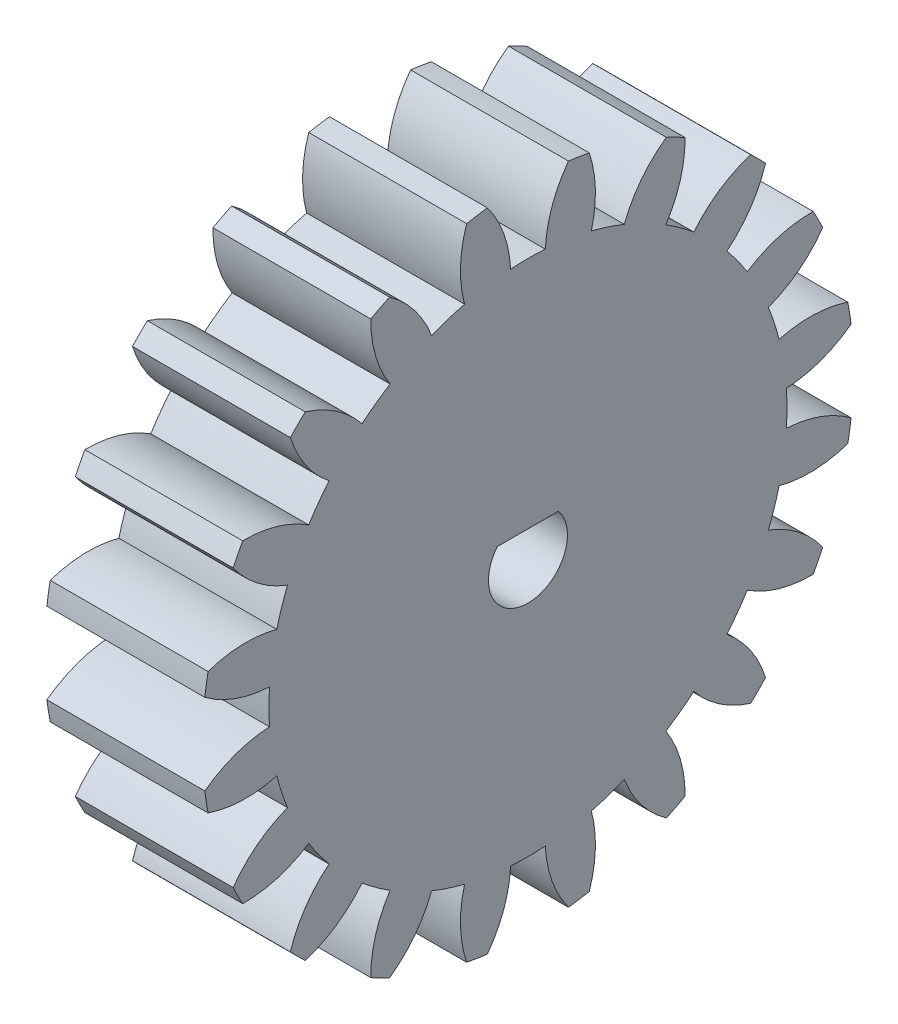
SolidWorks part; units mm, degrees
ref_plane "Plane1" through (0, 0, 0) normal (0, 0, 1) x (1, 0, 0)
ref_plane "Plane2" through (0, 0, 0) normal (0, 1, 0) x (1, 0, 0)
ref_plane "Plane3" through (0, 0, 0) normal (1, 0, 0) x (0, 0, -1)
sketch "HoldingSke" plane through (0, 0, 0) normal (0, 1, 0) x (1, 0, 0)
  line L0 (0, 0) -> (0.6265, -0.228)
  line L1 (-15, 0) -> (100, 0) construction
  line L2 (0, 0) -> (-2.1039, 2.3779)
  line L3 (0, 0) -> (-11.863, 4.5341)
  line L4 (0, 0) -> (8.1152, 2.9537)
  line L5 (0, 0) -> (-46.8476, -17.4728)
  line L6 (0, 0) -> (-6.6317, -4.4744)
  line L7 (-2.1039, 2.3779) -> (8.6586, 51.2059)
  line L8 (-76.2, 54.61) -> (-76.1, 54.61)
  line L9 (-67.7845, 28.3722) -> (-49.3413, 33.142)
  line L10 (-76.2, 71.12) -> (104.1128, 71.12)
  line L11 (0, 0) -> (-8, 0)
  line L12 (-76.2, 101.6) -> (-76.147, 101.6)
  line L13 (24.9733, 27.94) -> (52.9518, 28.4284)
  line L14 (24.9733, 27.94) -> (24.9743, 27.94)
  line L15 (24.9733, 27.94) -> (100.4006, 29.5858)
  line L16 (-63.627, -1.5) -> (-12.827, -1.5)
  circle A0 centre (0, 0) radius 0.4
  circle A1 centre (0, 0) radius 13.124
  circle A2 centre (0, 0) radius 37.5
  circle A3 centre (0, 0) radius 0.4
  dimension "MHD" = 26.248
  dimension "Hub_dia" = 75
  dimension "Bore" = 0.8
  dimension "MBD" = 0.8
  dimension "Num_teeth" = 20
  dimension "Pitch" = 0.6667
  dimension "Overall_len" = 50
  dimension "Show_teeth" = 20
  dimension "Thickness" = 8
  dimension "OAL" = 50.0001
  dimension "T_dim" = 0.1
  dimension "Ap" = 14.5
  dimension "H" = 19.05
  dimension "Pitch_radius" = 180.3128
  dimension "Width" = 8
  dimension "Backlash" = 0.053
  dimension "Addendum_fac" = 1
  dimension "Dedendum_fac" = 1.25
  dimension "Clearance_fac" = 0.25
  dimension "Dedendum_add" = 0.001
  dimension "Module" = 1.5
sketch "BasProSke" plane through (0, 0, 0) normal (0, 1, 0) x (1, 0, 0)
  line L0 (-10, 0) -> (60, 0) construction
  line L1 (0, 0) -> (0, 16.5)
  line L2 (0, 0) -> (8, 0)
  line L3 (8, 0) -> (8, 16.5)
  line L4 (8, 16.5) -> (0, 16.5)
  dimension "Thickness" = 8
  dimension "Diameter" = 33
revolve "Base-Revolve" add sketch "BasProSke" angle 360 about L0
sketch "TooCutSke" plane through (0, 0, 0) normal (1, 0, 0) x (0, 0, -1)
  line L1 (0, 0) -> (0, 107) construction
  line L2 (0, 0) -> (-1.2696, 14.9462) construction
  line L3 (0, 0) -> (-4.6808, 29.5532) construction
  line L4 (-1.2696, 14.9462) -> (-2.3404, 14.7766) construction
  arc A0 (0.8779, 13.0946) -> (-0.8779, 13.0946) centre (0, 0) ccw
  arc A1 (2.0711, 16.3951) -> (-2.0711, 16.3951) centre (0, 0) ccw
  circle A2 centre (0, 0) radius 15 construction
  circle A3 centre (0, 0) radius 14.5222 construction
  arc A4 (-0.8779, 13.0946) -> (-2.0711, 16.3951) centre (-6.8704, 12.7942) ccw
  arc A5 (2.0711, 16.3951) -> (0.8779, 13.0946) centre (6.8704, 12.7942) ccw
  dimension "Root_dia" = 26.248
  dimension "Overcut_dia" = 33.0508
  dimension "Pitch_dia" = 30
  dimension "Base_dia" = 29.0444
  dimension "Flank_rad" = 6
  dimension "Half_ang" = 9
  dimension "Half_CT" = 1.0841
extrude "ToothCut" cut sketch "TooCutSke" along normal through all
fillet "Breaks" [suppressed] radius 0.03
fillet "RootFillets" [suppressed] radius 0.376
pattern_circular "TeethCuts" count 20 every 18 about axis through (-10, 0, 0) along (1, 0, 0) of "ToothCut", "RootFillets", "Breaks"
sketch "HubNeaOneSke" plane through (0, 0, 0) normal (-1, 0, 0) x (0, 0, 1)
  circle A0 centre (0, 0) radius 13.124
  dimension "Diameter" = 26.248
extrude "HubNearOne" [suppressed] add sketch "HubNeaOneSke" along normal blind 42.0001
sketch "HubNeaBotSke" plane through (0, 0, 0) normal (-1, 0, 0) x (0, 0, 1)
  circle A0 centre (0, 0) radius 13.124
  dimension "Diameter" = 26.248
extrude "HubNearBoth" [suppressed] add sketch "HubNeaBotSke" along normal blind 21
ref_plane "FarPln" through (8, 0, 0) normal (1, 0, 0) x (0, 0, -1)
sketch "HubFarSke" plane through (8, 0, 0) normal (1, 0, 0) x (0, 0, -1)
  circle A0 centre (0, 0) radius 13.124
  dimension "Diameter" = 26.248
extrude "HubFar" [suppressed] add sketch "HubFarSke" along normal blind 21
sketch "BorSke" plane through (0, 0, 0) normal (1, 0, 0) x (0, 0, -1)
  circle A0 centre (0, 0) radius 0.4
  dimension "Diameter" = 0.8
extrude "Bore" cut sketch "BorSke" along normal mid plane 100.0001
sketch "KeySke" plane through (0, 0, 0) normal (1, 0, 0) x (0, 0, -1)
  line L0 (-0.05, 0) -> (-0.05, 0.5)
  line L1 (-0.05, 0.5) -> (0.05, 0.5)
  line L2 (0.05, 0.5) -> (0.05, 0)
  line L3 (0, 0) -> (0, 34) construction
  line L4 (-0.05, 0) -> (0.05, 0)
  dimension "Offset" = 0.5
  dimension "Width" = 0.1
extrude "Keyway" [suppressed] cut sketch "KeySke" along normal mid plane 100.0001
pattern_circular "Keyway2" [suppressed] count 2 every 90 about axis through (-10, 0, 0) along (1, 0, 0)
sketch "Sketch1" plane through (8, 0, 0) normal (1, 0, 0) x (0, 0, -1)
  line L0 (1.5537, 1.2594) -> (-1.5537, 1.2594)
  circle A0 centre (0, 0) radius 2
extrude "Cut-Extrude1" cut sketch "Sketch1" against normal through all contours L0 A0
equation "' \"Module@HoldingSke\" = 6.35"
equation "' \"Num_teeth@HoldingSke\" = 12"
equation "' \"Ap@HoldingSke\" =  20"
equation "' \"Ap@HoldingSke\" = 20"
equation "' \"Width@HoldingSke\" = 0.5 * 25.4"
equation "' \"Hub_dia@HoldingSke\"= 1 * 25.4"
equation "' \"Hub_dia@HoldingSke\" = 1 * 25.4"
equation "' \"Overall_len@HoldingSke\" = 1.0 * 25.4"
equation "' \"Bore@HoldingSke\" = 0.75 * 25.4"
equation "' \"T_dim@HoldingSke\" = 0.1 * 25.4"
equation "' \"Width@KeySke\" = 0.25 * 25.4"
equation "' \"Show_teeth@HoldingSke\" = 13"
equation "' \"Backlash@HoldingSke\" = 0.009 * 25.4"
equation "' \"Addendum_fac@HoldingSke\" = 1.0"
equation "' \"Dedendum_fac@HoldingSke\" = 1.25"
equation "' \"Dedendum_add@HoldingSke\" = 0.00005 * 25.4"
equation "' \"Clearance_fac@HoldingSke\" = 0.25"
equation "\"Pitch@HoldingSke\" = 1 / \"Module@HoldingSke\""
equation "\"Overcut_dia@TooCutSke\" = (\"Num_teeth@HoldingSke\" + 2 * \"Addendum_fac@HoldingSke\") / \"Pitch@HoldingSke\" + 0.002 * 25.4"
equation "\"Pitch_dia@TooCutSke\" = \"Num_teeth@HoldingSke\" / \"Pitch@HoldingSke\""
equation "\"Base_dia@TooCutSke\" = \"Num_teeth@HoldingSke\" / \"Pitch@HoldingSke\" * cos((\"Ap@HoldingSke\"  * 3.14159265 / 180))"
equation "\"Root_dia@TooCutSke\" = (\"Num_teeth@HoldingSke\" + 2) / \"Pitch@HoldingSke\" - 2 * (\"Addendum_fac@HoldingSke\" + \"Dedendum_fac@HoldingSke\") / \"Pitch@HoldingSke\" - \"Dedendum_add@HoldingSke\" * 2"
equation "\"Half_ang@TooCutSke\" = 180 / \"Num_teeth@HoldingSke\""
equation "\"Half_CT@TooCutSke\" = \"Num_teeth@HoldingSke\" / \"Pitch@HoldingSke\" * sin((3.14159265 / 2 / \"Num_teeth@HoldingSke\")) / 2 - 7 * \"Backlash@HoldingSke\" / 4"
equation "\"Flank_rad@TooCutSke\" = \"Num_teeth@HoldingSke\" / \"Pitch@HoldingSke\" / 5"
equation "\"Radius@RootFillets\" = \"Clearance_fac@HoldingSke\" / \"Pitch@HoldingSke\" + \"Dedendum_add@HoldingSke\""
equation "\"Break_rad@Breaks\" = 0.02 / \"Pitch@HoldingSke\""
equation "\"Thickness@HoldingSke\" = \"Width@HoldingSke\""
equation "\"OAL@HoldingSke\" = \"Thickness@HoldingSke\""
equation "\"MHD@HoldingSke\" = (\"Num_teeth@HoldingSke\" + 2) / \"Pitch@HoldingSke\" - 2 * (\"Addendum_fac@HoldingSke\" + \"Dedendum_fac@HoldingSke\")  / \"Pitch@HoldingSke\" - \"Dedendum_add@HoldingSke\" * 2"
equation "\"MBD@HoldingSke\" = (\"Num_teeth@HoldingSke\" + 2) / \"Pitch@HoldingSke\" - 2 * (\"Addendum_fac@HoldingSke\" + \"Dedendum_fac@HoldingSke\")  / \"Pitch@HoldingSke\" - \"Dedendum_add@HoldingSke\" * 2 - 0.002 * 25.4"
equation "\"MHD@HoldingSke\" = ((sgn( \"MHD@HoldingSke\" - \"Hub_dia@HoldingSke\" )-1)*( \"MHD@HoldingSke\" - \"Hub_dia@HoldingSke\" ))/-2+ \"Hub_dia@HoldingSke\""
equation "\"MBD@HoldingSke\" = ((sgn( \"MBD@HoldingSke\" - \"Bore@HoldingSke\" )-1)*( \"MBD@HoldingSke\" - \"Bore@HoldingSke\" ))/-2+ \"Bore@HoldingSke\""
equation "\"OAL@HoldingSke\" = ((sgn( \"OAL@HoldingSke\" - \"Overall_len@HoldingSke\" )+1)*( \"OAL@HoldingSke\" - \"Overall_len@HoldingSke\" ))/2 + \"Overall_len@HoldingSke\" + 0.000002 * 25.4"
equation "\"Num_teeth@TeethCuts\" = int( \"Show_teeth@HoldingSke\" ) + 1"
equation "\"Num_teeth@TeethCuts\" = ((sgn( \"Num_teeth@TeethCuts\" - \"Num_teeth@HoldingSke\" )-1)*( \"Num_teeth@TeethCuts\" - \"Num_teeth@HoldingSke\" ))/-2+ \"Num_teeth@HoldingSke\""
equation "\"Num_teeth@TeethCuts\" = ((sgn( \"Num_teeth@TeethCuts\" - 2.0)+1)*( \"Num_teeth@TeethCuts\" - 2.0))/2 +2.0"
equation "\"Angle@TeethCuts\" = 360.0 / \"Num_teeth@HoldingSke\""
equation "\"Diameter@BasProSke\" = (\"Num_teeth@HoldingSke\" + 2 * \"Addendum_fac@HoldingSke\") / \"Pitch@HoldingSke\""
equation "\"Thickness@BasProSke\"  = \"Thickness@HoldingSke\""
equation "' \"Fillet_rad@BasProSke\" =  \"Thickness@HoldingSke\" * 0.05"
equation "' \"Fillet_rad@BasProSke\" = \"Thickness@HoldingSke\" * 0.05"
equation "\"MHD@HoldingSke\" = ((sgn( \"MHD@HoldingSke\" - \"Root_dia@TooCutSke\" )-1)*( \"MHD@HoldingSke\" - \"Root_dia@TooCutSke\" ))/-2+ \"Root_dia@TooCutSke\""
equation "\"Diameter@HubNeaOneSke\" = \"MHD@HoldingSke\""
equation "\"Length@HubNearOne\" = \"OAL@HoldingSke\" - \"Thickness@BasProSke\""
equation "\"Diameter@HubNeaBotSke\" = \"MHD@HoldingSke\""
equation "\"Length@HubNearBoth\" = ( \"OAL@HoldingSke\" - \"Thickness@BasProSke\" ) / 2.0"
equation "\"Thickness@FarPln\" = \"Thickness@BasProSke\""
equation "\"Diameter@HubFarSke\" = \"MHD@HoldingSke\""
equation "\"Length@HubFar\" = ( \"OAL@HoldingSke\" - \"Thickness@BasProSke\" ) / 2.0"
equation "\"Diameter@BorSke\" = \"MBD@HoldingSke\""
equation "\"D1@Bore\" = \"OAL@HoldingSke\" * 2.0"
equation "\"D1@Keyway\" = \"OAL@HoldingSke\" * 2.0"
equation "\"Offset@KeySke\" = \"T_dim@HoldingSke\" + \"MBD@HoldingSke\" / 2.0"
